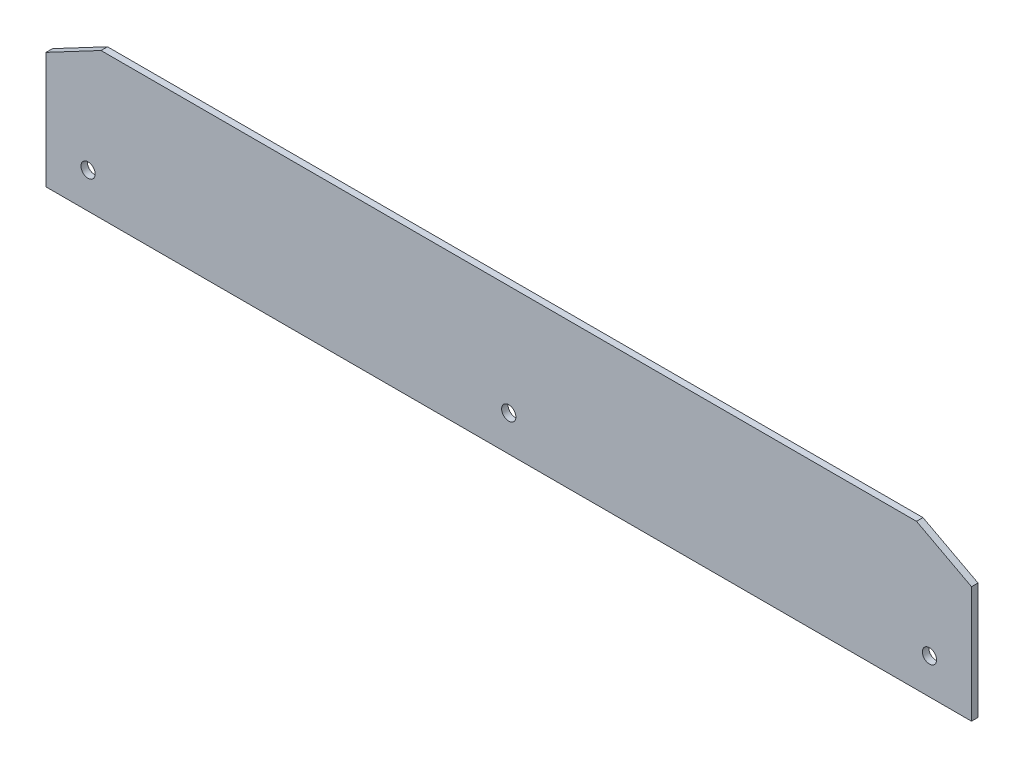
SolidWorks part; units mm, degrees
ref_plane "Front Plane" through (0, 0, 0) normal (0, 0, 1) x (1, 0, 0)
ref_plane "Top Plane" through (0, 0, 0) normal (0, 1, 0) x (1, 0, 0)
ref_plane "Right Plane" through (0, 0, 0) normal (1, 0, 0) x (0, 0, -1)
sketch "Low rear protection profile" plane through (0, 0, 0) normal (0, 0, 1) x (1, 0, 0)
  line L0 (-143, 7) -> (143, 7)
  line L1 (143, 7) -> (143, 43)
  line L2 (143, 43) -> (126, 52)
  line L3 (126, 52) -> (-126, 52)
  line L4 (-126, 52) -> (-143, 43)
  line L5 (-143, 43) -> (-143, 7)
  circle A0 centre (-130, 18) radius 2.2
  circle A1 centre (0, 18) radius 2.2
  circle A2 centre (130, 18) radius 2.2
extrude "Low rear protection" add sketch "Low rear protection profile" along normal blind 2
